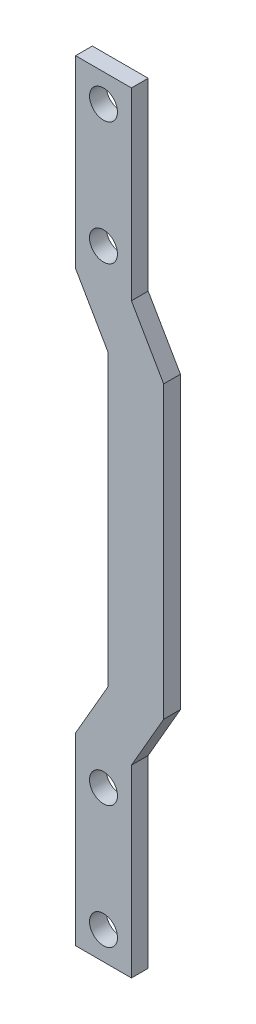
SolidWorks part; units mm, degrees
ref_plane "Plan de face" through (0, 0, 0) normal (0, 0, 1) x (1, 0, 0)
ref_plane "Plan de dessus" through (0, 0, 0) normal (0, 1, 0) x (1, 0, 0)
ref_plane "Plan de droite" through (0, 0, 0) normal (1, 0, 0) x (0, 0, -1)
sketch "Esquisse1" plane through (0, 0, 0) normal (0, 0, 1) x (1, 0, 0)
  line L0 (-105.0801, 63.2643) -> (-105.0801, 33.7643) construction
  line L2 (-100.0801, 30.2643) -> (-100.0801, 63.2643)
  line L3 (-100.0801, 63.2643) -> (-110.0801, 63.2643)
  line L4 (-110.0801, 30.2643) -> (-110.0801, 63.2643)
  line L5 (-110.0801, 30.2643) -> (-104.3066, 20.2643)
  line L6 (-100.0801, 30.2643) -> (-94.3066, 20.2643)
  line L7 (-104.3066, 20.2643) -> (-104.3066, -31.7357)
  line L8 (-94.3066, 20.2643) -> (-94.3066, -31.7357)
  line L9 (-154.4244, -5.7357) -> (-54.6434, -5.7357) construction
  line L10 (-100.0801, -74.7357) -> (-110.0801, -74.7357)
  line L12 (-110.0801, -41.7357) -> (-110.0801, -74.7357)
  line L13 (-100.0801, -41.7357) -> (-100.0801, -74.7357)
  line L14 (-110.0801, -41.7357) -> (-104.3066, -31.7357)
  line L15 (-100.0801, -41.7357) -> (-94.3066, -31.7357)
  circle A0 centre (-105.0801, 58.2643) radius 2.5
  circle A1 centre (-105.0801, 36.2643) radius 2.5
  circle A2 centre (-105.0801, -47.7357) radius 2.5
  circle A3 centre (-105.0801, -69.7357) radius 2.5
  point P14 (-104.3066, -5.7357)
  point P26 (-94.3066, -5.7357)
  dimension "D3" = 5
  dimension "D5" = 5
  dimension "D1" = 10
  dimension "D2" = 33
  dimension "D4" = 5
  dimension "D6" = 22
  dimension "D7" = 10
  dimension "D8" = 10
  dimension "D9" = 30
  dimension "D10" = 30
  dimension "D11" = 26
extrude "Boss.-Extru.1" add sketch "Esquisse1" along normal blind 3
